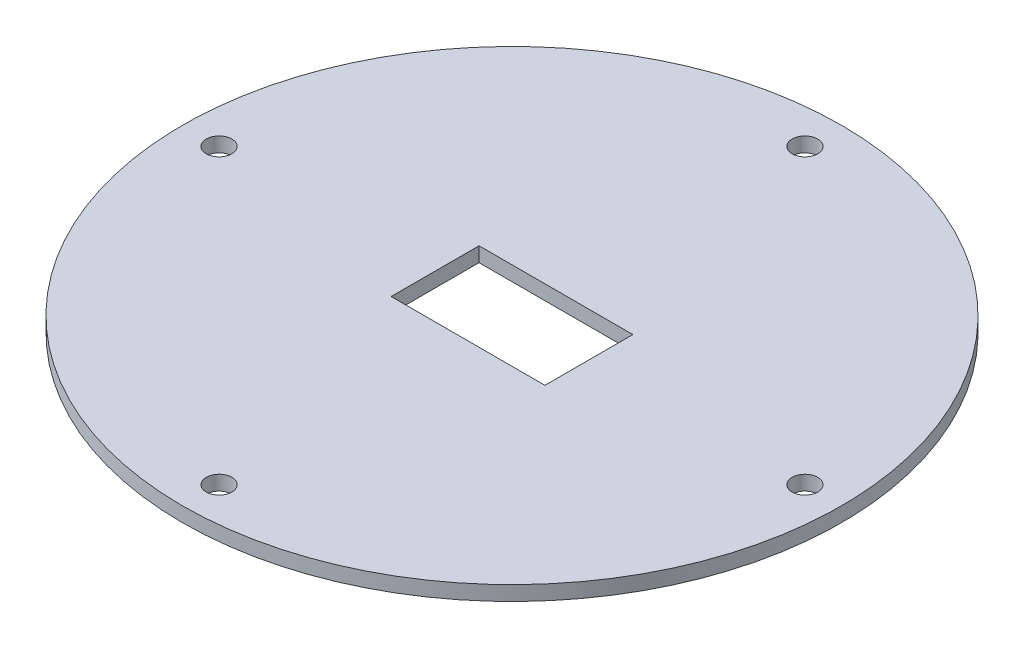
SolidWorks part; units mm, degrees
ref_plane "Front Plane" through (0, 0, 0) normal (0, 0, 1) x (1, 0, 0)
ref_plane "Top Plane" through (0, 0, 0) normal (0, 1, 0) x (1, 0, 0)
ref_plane "Right Plane" through (0, 0, 0) normal (1, 0, 0) x (0, 0, -1)
sketch "Sketch1" plane through (0, 0, 0) normal (0, 1, 0) x (1, 0, 0)
  circle A0 centre (0, 0) radius 45
  dimension "D1" = 90
extrude "Boss-Extrude1" add sketch "Sketch1" along normal blind 2 contours A0
sketch "Sketch2" plane through (0, 2, 0) normal (0, 1, 0) x (1, 0, 0)
  circle A0 centre (0, 40) radius 1.75
  circle A1 centre (40, 0) radius 1.75
  circle A2 centre (0, -40) radius 1.75
  circle A3 centre (-40, 0) radius 1.75
  circle A4 centre (0, 0) radius 45 construction
  point P11 (0, 0)
  dimension "D1" = 40
  dimension "D2" = 3.5
  dimension "D3" = 4
extrude "Cut-Extrude1" cut sketch "Sketch2" against normal through all
sketch "Sketch3" plane through (0, 2, 0) normal (0, 1, 0) x (1, 0, 0)
  line L1 (-10.5, -6) -> (10.5, -6)
  line L2 (-10.5, -6) -> (-10.5, 6)
  line L3 (-10.5, 6) -> (10.5, 6)
  line L4 (10.5, -6) -> (10.5, 6)
  line L5 (-10.5, -6) -> (10.5, 6) construction
  line L6 (-10.5, 6) -> (10.5, -6) construction
  point P0 (0, 0)
  dimension "D1" = 12
  dimension "D2" = 21
extrude "Cut-Extrude2" cut sketch "Sketch3" against normal through all
